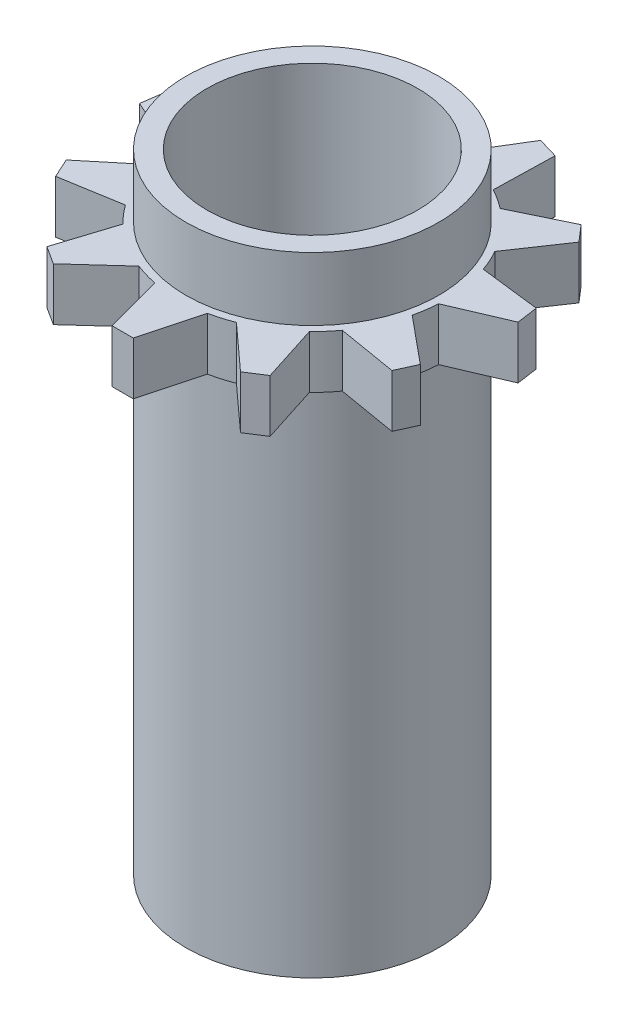
SolidWorks part; units mm, degrees
ref_plane "Front Plane" through (0, 0, 0) normal (0, 0, 1) x (1, 0, 0)
ref_plane "Top Plane" through (0, 0, 0) normal (0, 1, 0) x (1, 0, 0)
ref_plane "Right Plane" through (0, 0, 0) normal (1, 0, 0) x (0, 0, -1)
sketch "Sketch1" plane through (0, 0, 0) normal (0, 1, 0) x (1, 0, 0)
  circle A0 centre (0, 0) radius 6
  dimension "D1" = 12
extrude "Boss-Extrude1" add sketch "Sketch1" along normal blind 24.3
sketch "Sketch8" plane through (0, 24.3, 0) normal (0, 1, 0) x (-1, 0, 0)
  circle A0 centre (0, 0) radius 6.35
  dimension "D1" = 12.7
extrude "Boss-Extrude5" add sketch "Sketch8" along normal blind 2.5
sketch "Sketch9" plane through (0, 26.8, 0) normal (0, 1, 0) x (1, 0, 0)
  line L0 (0, 0) -> (0, -12.192) construction
  line L1 (0.508, -9) -> (-0.508, -9)
  line L2 (0, 0) -> (-6.35, 0) construction
  line L3 (1.2861, -6.096) -> (-1.2861, -6.096)
  line L4 (1.2861, -6.096) -> (0.508, -9)
  line L5 (-0.508, -9) -> (-1.2861, -6.096)
  circle A0 centre (0, 0) radius 6.35 construction
  point P6 (0, -9)
  dimension "D1" = 9
  dimension "D2" = 6.096
  dimension "D3" = 75
  dimension "D4" = 1.016
extrude "Boss-Extrude6" add sketch "Sketch9" against normal blind 2.5
pattern_circular "CirPattern1" count 11 over 360 about axis through (0, 0, 0) along (0, 1, 0) of "Boss-Extrude6"
sketch "Sketch10" plane through (0, 26.8, 0) normal (0, 1, 0) x (1, 0, 0)
  circle A0 centre (0, 0) radius 6
  dimension "D1" = 12
extrude "Boss-Extrude7" add sketch "Sketch10" along normal blind 3
sketch "Sketch11" plane through (0, 29.8, 0) normal (0, 1, 0) x (-1, 0, 0)
  circle A0 centre (0, 0) radius 5
  dimension "D1" = 10
extrude "Cut-Extrude3" cut sketch "Sketch11" against normal through all both and the other way through all
